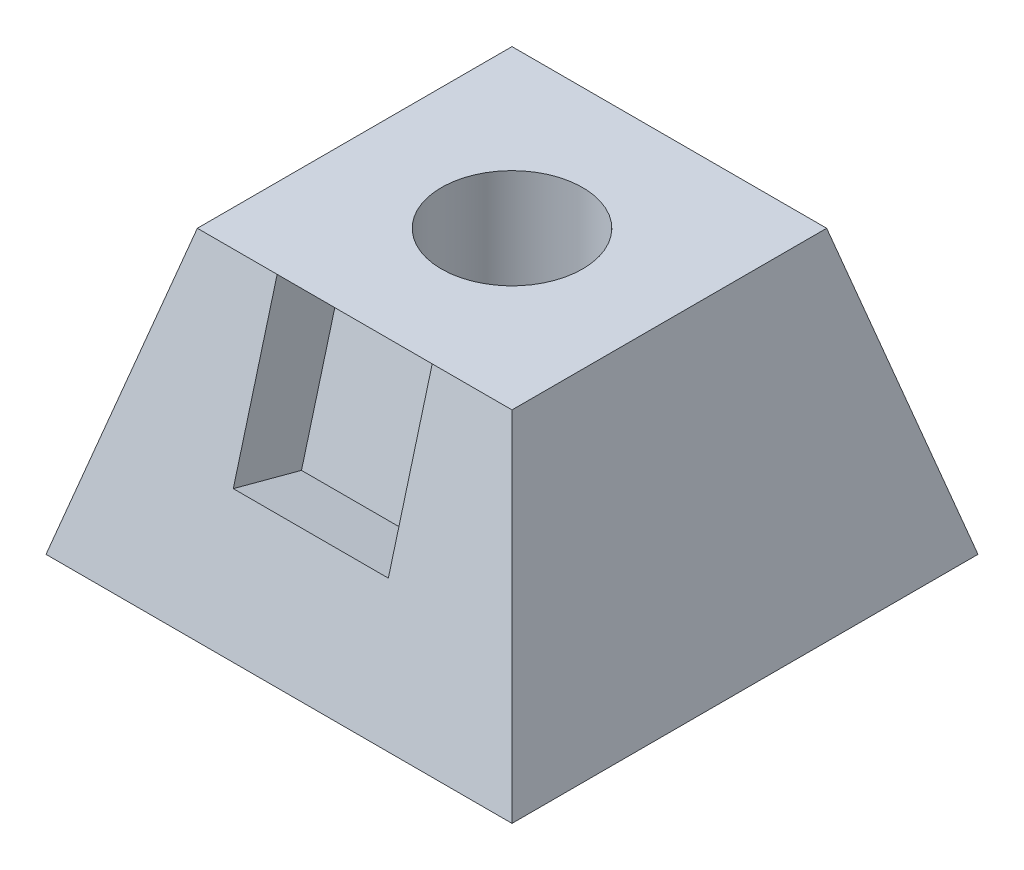
SolidWorks part; units mm, degrees
ref_plane "Front Plane" through (0, 0, 0) normal (0, 0, 1) x (1, 0, 0)
ref_plane "Top Plane" through (0, 0, 0) normal (0, 1, 0) x (1, 0, 0)
ref_plane "Right Plane" through (0, 0, 0) normal (1, 0, 0) x (0, 0, -1)
sketch "Sketch1" plane through (0, 0, 0) normal (0, 1, 0) x (1, 0, 0)
  line L1 (-165, -165) -> (165, -165)
  line L2 (-165, -165) -> (-165, 165)
  line L3 (-165, 165) -> (165, 165)
  line L4 (165, -165) -> (165, 165)
  line L5 (-165, -165) -> (165, 165) construction
  line L6 (-165, 165) -> (165, -165) construction
  point P0 (0, 0)
  dimension "D1" = 330
  dimension "D2" = 330
extrude "Boss-Extrude1" add sketch "Sketch1" along normal blind 200 draft 15 contours L3 L4 L1 L2
sketch "Sketch2" plane through (0, 200, 0) normal (0, 1, 0) x (1, 0, 0)
  line L4 (-111.4102, 111.4102) -> (111.4102, 111.4102) construction
  circle A0 centre (0, 0) radius 50
extrude "Cut-Extrude1" cut sketch "Sketch2" against normal blind 170
sketch "Sketch7" plane through (0, 41.25, 153.9471) normal (0, 0.2588, 0.9659) x (1, 0, 0)
  line L0 (-111.4102, 164.3501) -> (111.4102, 164.3501) construction
  line L1 (-54.9, 44.3501) -> (54.9, 44.3501)
  line L2 (-54.9, 44.3501) -> (-54.9, 164.3501)
  line L3 (-54.9, 164.3501) -> (54.9, 164.3501)
  line L4 (54.9, 44.3501) -> (54.9, 164.3501)
  line L5 (-54.9, 44.3501) -> (54.9, 164.3501) construction
  line L6 (-54.9, 164.3501) -> (54.9, 44.3501) construction
  line L7 (-111.4102, 222.0202) -> (111.4102, 222.0202) construction
  point P0 (0, 104.3501)
  point P7 (0, 164.3501)
  point P10 (0, 222.0202)
  dimension "D1" = 109.8
  dimension "D2" = 120
extrude "Cut-Extrude2" cut sketch "Sketch7" against normal blind 50
sketch "Sketch12" plane through (0, 41.25, -153.9471) normal (0, 0.2588, -0.9659) x (-1, 0, 0)
  line L0 (-111.4102, 164.3501) -> (111.4102, 164.3501)
  line L1 (111.4102, 164.3501) -> (165, -42.7051)
  line L2 (165, -42.7051) -> (-165, -42.7051)
  line L3 (-165, -42.7051) -> (-111.4102, 164.3501)
  dimension "D1" = 330
  dimension "D2" = 213.8779
  dimension "D3" = 222.8203
sketch "Sketch13" plane through (0, 200, 0) normal (0, 1, 0) x (1, 0, 0)
  line L0 (-111.4102, 111.4102) -> (-111.4102, -111.4102)
  line L1 (-111.4102, -111.4102) -> (111.4102, -111.4102)
  line L2 (111.4102, -111.4102) -> (111.4102, 111.4102)
  line L3 (111.4102, 111.4102) -> (-111.4102, 111.4102)
  circle A0 centre (0, 0) radius 50
  dimension "D3" = 100
  dimension "D1" = 222.8203
  dimension "D2" = 222.8203
